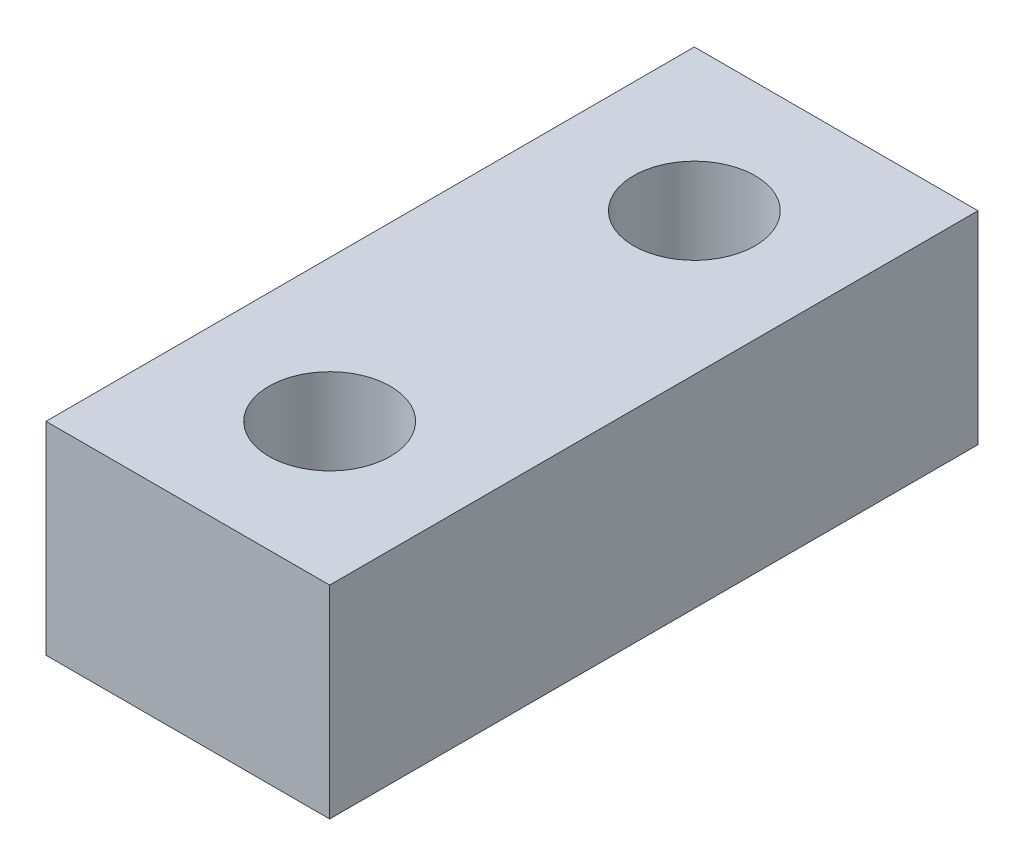
SolidWorks part; units mm, degrees
ref_plane "Piano frontale" through (0, 0, 0) normal (0, 0, 1) x (1, 0, 0)
ref_plane "Piano superiore" through (0, 0, 0) normal (0, 1, 0) x (1, 0, 0)
ref_plane "Piano destro" through (0, 0, 0) normal (1, 0, 0) x (0, 0, -1)
sketch "Schizzo1" plane through (0, 0, 0) normal (0, 0, 1) x (1, 0, 0)
  line L0 (0, 0) -> (-7, 0)
  line L1 (-7, 0) -> (-7, 5)
  line L2 (-7, 5) -> (0, 5)
  line L3 (0, 5) -> (0, 0)
  dimension "D1" = 7
  dimension "D2" = 5
extrude "Estrusione-Estrusione1" add sketch "Schizzo1" along normal blind 16
sketch "Schizzo2" plane through (0, 0, 0) normal (0, -1, 0) x (-1, 0, 0)
  line L0 (7, 0) -> (0, 0) construction
  line L1 (3.5, -16) -> (3.5, 3.3709) construction
  line L2 (7, -16) -> (0, -16) construction
  circle A0 centre (3.5, -12.5) radius 1.5
  circle A1 centre (3.5, -3.5) radius 1.5
  dimension "D3" = 3
  dimension "D1" = 9
  dimension "D2" = 3.5
extrude "Taglio-Estrusione1" cut sketch "Schizzo2" against normal through all
